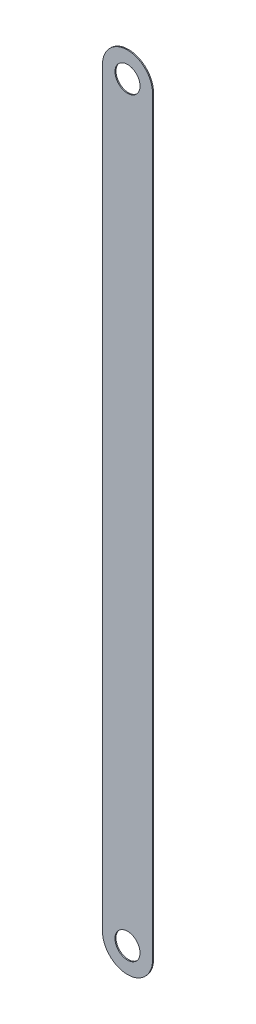
SolidWorks part; units mm, degrees
ref_plane "Front Plane" through (0, 0, 0) normal (0, 0, 1) x (1, 0, 0)
ref_plane "Top Plane" through (0, 0, 0) normal (0, 1, 0) x (1, 0, 0)
ref_plane "Right Plane" through (0, 0, 0) normal (1, 0, 0) x (0, 0, -1)
sketch "Sketch2" plane through (0, 0, 0) normal (0, 0, 1) x (1, 0, 0)
  line L0 (0, 190.5) -> (0, 0) construction
  line L1 (6.35, 190.5) -> (6.35, 0)
  line L2 (-6.35, 190.5) -> (-6.35, 0)
  arc A0 (6.35, 190.5) -> (-6.35, 190.5) centre (0, 190.5) ccw
  arc A1 (-6.35, 0) -> (6.35, 0) centre (0, 0) ccw
  circle A2 centre (0, 190.5) radius 3.175
  circle A3 centre (0, 0) radius 3.175
  point P3 (0, 95.25)
  dimension "D3" = 6.35
  dimension "D4" = 6.35
  dimension "D1" = 12.7
  dimension "D2" = 190.5
extrude "Boss-Extrude1" add sketch "Sketch2" along normal blind 0.254
